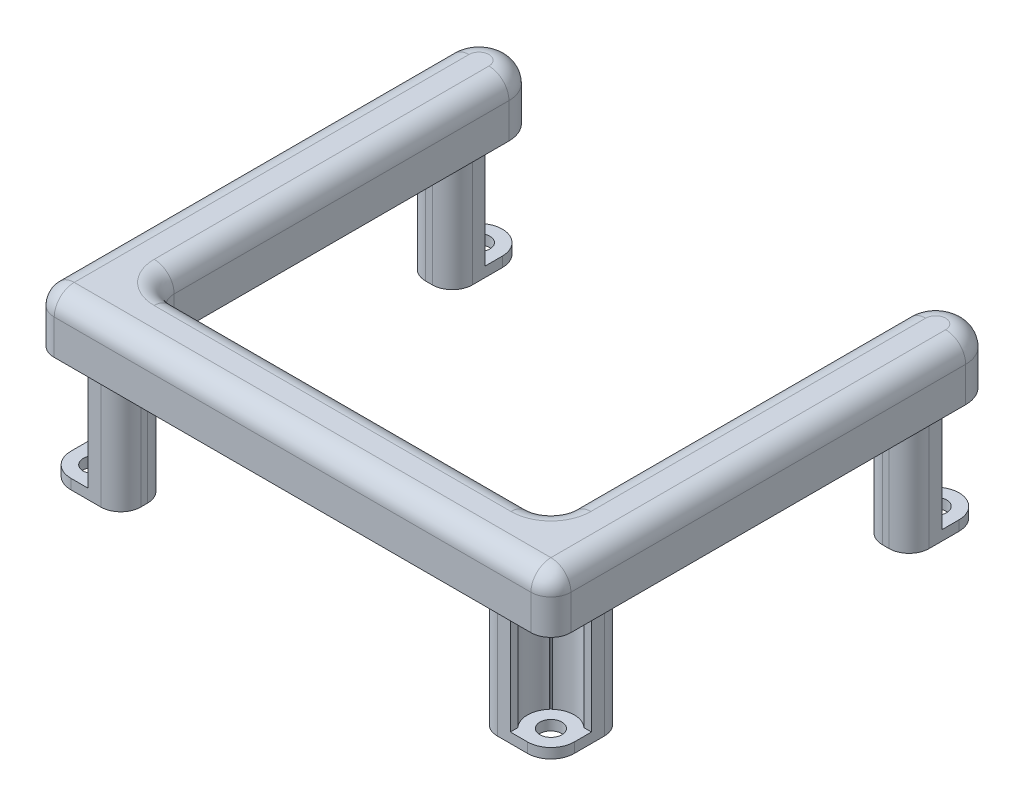
SolidWorks part; units mm, degrees
ref_plane "Front Plane" through (0, 0, 0) normal (0, 0, 1) x (1, 0, 0)
ref_plane "Top Plane" through (0, 0, 0) normal (0, 1, 0) x (1, 0, 0)
ref_plane "Right Plane" through (0, 0, 0) normal (1, 0, 0) x (0, 0, -1)
sketch "Sketch1" plane through (0, 0, 0) normal (0, 1, 0) x (1, 0, 0)
  line L0 (-1.397, 0) -> (59.436, 0) construction
  line L1 (0, -1.397) -> (0, 50.292) construction
  line L2 (29.0195, -1.397) -> (29.0195, 50.292) construction
  line L3 (59.436, 24.4475) -> (-1.397, 24.4475) construction
  circle A0 centre (0, 0) radius 2.9718
  circle A1 centre (0, 0) radius 1.397
  circle A2 centre (58.039, 0) radius 1.397
  circle A3 centre (58.039, 0) radius 2.9718
  circle A4 centre (58.039, 48.895) radius 2.9718
  circle A5 centre (58.039, 48.895) radius 1.397
  circle A6 centre (0, 48.895) radius 1.397
  circle A7 centre (0, 48.895) radius 2.9718
  point P14 (0, 24.4475)
  point P15 (29.0195, 0)
  dimension "D1" = 5.9436
  dimension "D2" = 2.794
  dimension "D3" = 60.833
  dimension "D4" = 51.689
extrude "Boss-Extrude1" add sketch "Sketch1" along normal blind 1.27
ref_plane "Plane1" through (0, 14.351, 0) normal (0, -1, 0) x (-1, 0, 0)
sketch "Sketch2" plane through (0, 14.351, 0) normal (0, 1, 0) x (1, 0, 0)
  line L0 (0, 48.895) -> (0, 0) construction
  line L1 (0, 0) -> (58.039, 0) construction
  line L2 (58.039, 0) -> (58.039, 48.895) construction
  line L3 (-3.81, 48.895) -> (-3.81, -1.27)
  line L4 (-1.27, -3.81) -> (59.309, -3.81)
  line L5 (61.849, -1.27) -> (61.849, 48.895)
  line L6 (3.81, 48.895) -> (3.81, 6.35)
  line L7 (6.35, 3.81) -> (51.689, 3.81)
  line L8 (54.229, 6.35) -> (54.229, 48.895)
  line L9 (3.81, 48.895) -> (3.81, 3.81) construction
  line L10 (3.81, 3.81) -> (54.229, 3.81) construction
  line L11 (54.229, 3.81) -> (54.229, 48.895) construction
  line L12 (61.849, -3.81) -> (61.849, 48.895) construction
  line L13 (-3.81, -3.81) -> (61.849, -3.81) construction
  line L14 (-3.81, 48.895) -> (-3.81, -3.81) construction
  arc A0 (-3.81, 48.895) -> (3.81, 48.895) centre (0, 48.895) cw
  arc A1 (61.849, 48.895) -> (54.229, 48.895) centre (58.039, 48.895) ccw
  arc A2 (3.81, 6.35) -> (6.35, 3.81) centre (6.35, 6.35) ccw
  arc A3 (51.689, 3.81) -> (54.229, 6.35) centre (51.689, 6.35) ccw
  arc A4 (61.849, -1.27) -> (59.309, -3.81) centre (59.309, -1.27) cw
  arc A5 (-1.27, -3.81) -> (-3.81, -1.27) centre (-1.27, -1.27) cw
  dimension "D3" = 2.54
  dimension "D1" = 3.81
  dimension "D2" = 3.81
extrude "Boss-Extrude2" add sketch "Sketch2" along normal blind 6.985
fillet "Fillet1" radius 2.54 12 edges at (29.0195, 21.336, -3.81) (4.5539, 21.336, -4.5539) (3.81, 21.336, -27.6225) (0, 21.336, -52.705) (-3.81, 21.336, -23.8125) (-3.0661, 21.336, 3.0661) (29.0195, 21.336, 3.81) (61.1051, 21.336, 3.0661) (53.4851, 21.336, -4.5539) (54.229, 21.336, -27.6225) (58.039, 21.336, -52.705) (61.849, 21.336, -23.8125)
sketch "Sketch3" plane through (0, 0, 0) normal (0, -1, 0) x (1, 0, 0)
  line L0 (-1.397, -48.895) -> (-2.9718, -48.895)
  line L1 (0.4318, -42.545) -> (-0.4318, -42.545)
  line L2 (2.9718, -45.085) -> (2.9718, -48.895)
  line L3 (2.9718, -48.895) -> (1.397, -48.895)
  line L4 (-2.9718, -45.085) -> (-2.9718, -48.895)
  line L5 (58.039, 1.397) -> (58.039, -1.397) construction
  line L6 (-1.397, -24.4475) -> (59.436, -24.4475) construction
  line L7 (29.0195, -50.292) -> (29.0195, 1.397) construction
  line L8 (-2.9718, -3.81) -> (-2.9718, 0)
  line L9 (55.0672, -2.9718) -> (55.0672, 2.9718) construction
  line L10 (2.9718, -3.81) -> (2.9718, -2.9718)
  line L11 (0.4318, -6.35) -> (-0.4318, -6.35)
  line L12 (-1.397, 0) -> (-2.9718, 0)
  line L13 (59.436, 0) -> (61.0108, 0)
  line L14 (57.6072, -6.35) -> (58.4708, -6.35)
  line L15 (55.0672, -3.81) -> (55.0672, -2.9718)
  line L16 (55.0672, -2.9718) -> (61.0108, -2.9718) construction
  line L17 (61.0108, -3.81) -> (61.0108, 0)
  line L18 (61.0108, -45.085) -> (61.0108, -48.895)
  line L19 (55.0672, -48.895) -> (56.642, -48.895)
  line L20 (55.0672, -45.085) -> (55.0672, -48.895)
  line L21 (57.6072, -42.545) -> (58.4708, -42.545)
  line L22 (59.436, -48.895) -> (61.0108, -48.895)
  line L23 (51.689, 0.4318) -> (55.0672, 0.4318) construction
  line L24 (51.689, 0.4318) -> (51.689, -0.4318)
  line L25 (54.229, 2.9718) -> (58.039, 2.9718)
  line L26 (58.039, 2.9718) -> (58.039, 1.397)
  line L27 (54.229, -2.9718) -> (55.0672, -2.9718)
  line L28 (0, 1.397) -> (0, -1.397) construction
  line L29 (3.81, -2.9718) -> (2.9718, -2.9718)
  line L30 (0, 2.9718) -> (0, 1.397)
  line L31 (3.81, 2.9718) -> (0, 2.9718)
  line L32 (6.35, 0.4318) -> (6.35, -0.4318)
  line L33 (59.436, 0) -> (56.642, 0) construction
  line L34 (2.9718, -2.9718) -> (2.9718, 2.9718) construction
  line L35 (51.689, -0.4318) -> (55.0672, -0.4318) construction
  line L36 (-1.397, 0) -> (1.397, 0) construction
  circle A0 centre (0, -48.895) radius 2.9718 construction
  arc A1 (-1.397, -48.895) -> (1.397, -48.895) centre (0, -48.895) cw
  arc A2 (-2.9718, -45.085) -> (-0.4318, -42.545) centre (-0.4318, -45.085) cw
  arc A3 (0.4318, -42.545) -> (2.9718, -45.085) centre (0.4318, -45.085) cw
  circle A4 centre (0, -48.895) radius 1.397 construction
  arc A5 (0.4318, -6.35) -> (2.9718, -3.81) centre (0.4318, -3.81) ccw
  arc A6 (-2.9718, -3.81) -> (-0.4318, -6.35) centre (-0.4318, -3.81) ccw
  arc A7 (-1.397, 0) -> (0, 1.397) centre (0, 0) ccw
  arc A8 (59.436, 0) -> (58.039, 1.397) centre (58.039, 0) cw
  arc A9 (61.0108, -3.81) -> (58.4708, -6.35) centre (58.4708, -3.81) cw
  arc A10 (57.6072, -6.35) -> (55.0672, -3.81) centre (57.6072, -3.81) cw
  arc A11 (57.6072, -42.545) -> (55.0672, -45.085) centre (57.6072, -45.085) ccw
  arc A12 (61.0108, -45.085) -> (58.4708, -42.545) centre (58.4708, -45.085) ccw
  arc A13 (59.436, -48.895) -> (56.642, -48.895) centre (58.039, -48.895) ccw
  arc A15 (54.229, -2.9718) -> (51.689, -0.4318) centre (54.229, -0.4318) cw
  arc A16 (51.689, 0.4318) -> (54.229, 2.9718) centre (54.229, 0.4318) cw
  circle A17 centre (58.039, 0) radius 2.9718 construction
  circle A18 centre (58.039, 0) radius 1.397 construction
  arc A19 (6.35, 0.4318) -> (3.81, 2.9718) centre (3.81, 0.4318) ccw
  arc A20 (3.81, -2.9718) -> (6.35, -0.4318) centre (3.81, -0.4318) ccw
  dimension "D1" = 2.54
  dimension "D2" = 6.35
extrude "Boss-Extrude3" add sketch "Sketch3" against normal blind 1.27
sketch "Sketch4" plane through (0, 1.27, 0) normal (0, 1, 0) x (1, 0, 0)
  line L0 (-2.9718, 45.085) -> (-2.9718, 48.895) construction
  line L1 (-2.9718, 46.7106) -> (-2.0149, 46.7106)
  line L2 (-2.9718, 46.7106) -> (-2.9718, 45.085)
  line L3 (-0.4318, 42.545) -> (0.4318, 42.545)
  line L4 (2.9718, 46.7106) -> (2.9718, 45.085)
  line L5 (2.9718, 48.895) -> (2.9718, 45.085) construction
  line L6 (0, 47.498) -> (0, 45.9232) construction
  line L7 (0.4318, 42.545) -> (-0.4318, 42.545) construction
  line L8 (0, 50.292) -> (0, 51.8668) construction
  line L9 (2.0149, 46.7106) -> (2.9718, 46.7106)
  line L10 (-2.0149, 46.7106) -> (2.0149, 46.7106) construction
  line L11 (-1.397, 24.4475) -> (59.436, 24.4475) construction
  line L12 (29.0195, 50.292) -> (29.0195, -1.397) construction
  line L13 (59.436, 24.4475) -> (-1.397, 24.4475) construction
  line L14 (29.0195, -1.397) -> (29.0195, 50.292) construction
  line L15 (60.0539, 46.7106) -> (56.0241, 46.7106) construction
  line L16 (58.039, 50.292) -> (58.039, 51.8668) construction
  line L17 (58.039, 47.498) -> (58.039, 45.9232) construction
  line L18 (56.0241, 46.7106) -> (55.0672, 46.7106)
  line L19 (55.0672, 46.7106) -> (55.0672, 45.085)
  line L20 (58.4708, 42.545) -> (57.6072, 42.545)
  line L21 (61.0108, 46.7106) -> (61.0108, 45.085)
  line L22 (61.0108, 46.7106) -> (60.0539, 46.7106)
  line L23 (-2.0149, 2.1844) -> (2.0149, 2.1844) construction
  line L24 (0, -1.397) -> (0, -2.9718) construction
  line L25 (0, 1.397) -> (0, 2.9718) construction
  line L26 (2.0149, 2.1844) -> (2.1844, 2.1844)
  line L27 (2.9718, 2.9718) -> (2.9718, 3.81)
  line L28 (-0.4318, 6.35) -> (0.4318, 6.35)
  line L29 (-2.9718, 2.1844) -> (-2.9718, 3.81)
  line L30 (-2.9718, 2.1844) -> (-2.0149, 2.1844)
  line L32 (58.4708, 6.35) -> (58.4708, 2.1844) construction
  line L33 (58.039, 1.397) -> (58.039, 2.9718) construction
  line L34 (58.039, -1.397) -> (58.039, -2.9718) construction
  line L35 (60.0539, 2.1844) -> (56.0241, 2.1844) construction
  line L36 (55.8546, 2.0149) -> (55.8546, 2.1844)
  line L37 (51.689, -0.4318) -> (51.689, 0.4318)
  line L38 (55.0672, 2.9718) -> (54.229, 2.9718)
  line L39 (3.81, -2.9718) -> (0, -2.9718) construction
  line L40 (2.1844, -2.9718) -> (3.81, -2.9718)
  line L41 (2.1844, -2.9718) -> (2.1844, -2.0149)
  line L42 (2.9718, 2.9718) -> (3.81, 2.9718)
  line L43 (6.35, -0.4318) -> (6.35, 0.4318)
  line L44 (2.9718, 2.9718) -> (3.81, 2.9718) construction
  line L45 (6.35, 0.4318) -> (6.35, -0.4318) construction
  line L46 (-0.4318, 6.35) -> (-0.4318, 2.1844) construction
  line L48 (2.1844, 2.0149) -> (2.1844, 2.1844)
  line L49 (55.8546, -2.9718) -> (55.8546, -2.0149)
  line L50 (55.8546, -2.9718) -> (54.229, -2.9718)
  line L51 (61.0108, 2.1844) -> (60.0539, 2.1844)
  line L52 (61.0108, 2.1844) -> (61.0108, 3.81)
  line L53 (58.4708, 6.35) -> (57.6072, 6.35)
  line L54 (55.0672, 2.9718) -> (55.0672, 3.81)
  line L55 (56.0241, 2.1844) -> (55.8546, 2.1844)
  arc A0 (2.9718, 45.085) -> (0.4318, 42.545) centre (0.4318, 45.085) cw
  arc A1 (-0.4318, 42.545) -> (-2.9718, 45.085) centre (-0.4318, 45.085) cw
  arc A2 (-2.0149, 46.7106) -> (2.0149, 46.7106) centre (0, 48.895) ccw
  circle A3 centre (0, 48.895) radius 1.397 construction
  circle A4 centre (58.039, 48.895) radius 2.9718 construction
  circle A5 centre (0, 48.895) radius 2.9718 construction
  arc A6 (2.9718, 48.895) -> (-2.9718, 48.895) centre (0, 48.895) ccw construction
  arc A7 (60.0539, 46.7106) -> (56.0241, 46.7106) centre (58.039, 48.895) cw
  arc A8 (58.4708, 42.545) -> (61.0108, 45.085) centre (58.4708, 45.085) ccw
  arc A9 (55.0672, 45.085) -> (57.6072, 42.545) centre (57.6072, 45.085) ccw
  circle A10 centre (0, 0) radius 2.9718 construction
  arc A11 (-2.0149, 2.1844) -> (2.0149, 2.1844) centre (0, 0) cw
  arc A12 (-0.4318, 6.35) -> (-2.9718, 3.81) centre (-0.4318, 3.81) ccw
  arc A13 (2.9718, 3.81) -> (0.4318, 6.35) centre (0.4318, 3.81) ccw
  circle A14 centre (58.039, 0) radius 2.9718 construction
  arc A15 (51.689, 0.4318) -> (54.229, 2.9718) centre (54.229, 0.4318) cw
  arc A16 (54.229, -2.9718) -> (51.689, -0.4318) centre (54.229, -0.4318) cw
  arc A17 (55.8546, -2.0149) -> (55.8546, 2.0149) centre (58.039, 0) cw
  arc A18 (2.1844, -2.0149) -> (2.1844, 2.0149) centre (0, 0) ccw
  arc A19 (3.81, -2.9718) -> (6.35, -0.4318) centre (3.81, -0.4318) ccw
  arc A20 (6.35, 0.4318) -> (3.81, 2.9718) centre (3.81, 0.4318) ccw
  arc A21 (55.0672, 3.81) -> (57.6072, 6.35) centre (57.6072, 3.81) cw
  arc A22 (58.4708, 6.35) -> (61.0108, 3.81) centre (58.4708, 3.81) cw
  arc A23 (60.0539, 2.1844) -> (56.0241, 2.1844) centre (58.039, 0) ccw
  point P24 (0, 46.7106)
  dimension "D1" = 2.54
  dimension "D2" = 2.54
extrude "Boss-Extrude4" add sketch "Sketch4" along normal up to surface (13.081 mm away) up to face at (29.0195, 14.351, -17.6046)
equation "\"rasPiHoleDiam\"=0.11"
equation "\"rasPiHolHorBet\"=2.035"
equation "\"rasPiHolVerBet\"=2.395"
equation "\"housingStabbyHeights\"=0.395"
equation "\"housingChannelWidth\"= 0.55"
equation "\"housingChannelHeight\"=0.275"
equation "\"housingPiStandOff\"=0.234"
equation "\"housingPiStandOffHeight\"=0.15"
equation "\"D1@Sketch1\"=\"housingPiStandOff\""
equation "\"D2@Sketch1\"=\"rasPiHoleDiam\""
equation "\"housingTopStandOff\"=0.565"
equation "\"servoHatHolHorBet\"=2.395"
equation "\"rasPiHolVerrBet\"=2.035"
equation "\"D3@Sketch1\"=\"rasPiHolVerBet\""
equation "\"servoHatHolVerBet\"=2.038"
equation "\"D4@Sketch1\" = \"rasPiHolHorBet\""
equation "\"housingTopChannelWidth\"=0.3"
equation "\"D1@Sketch2\"=\"housingTopChannelWidth\"/2"
equation "\"D1@Boss-Extrude2\"=\"housingChannelHeight\""
equation "\"D1@Plane1\"= \"housingTopStandOff\""
